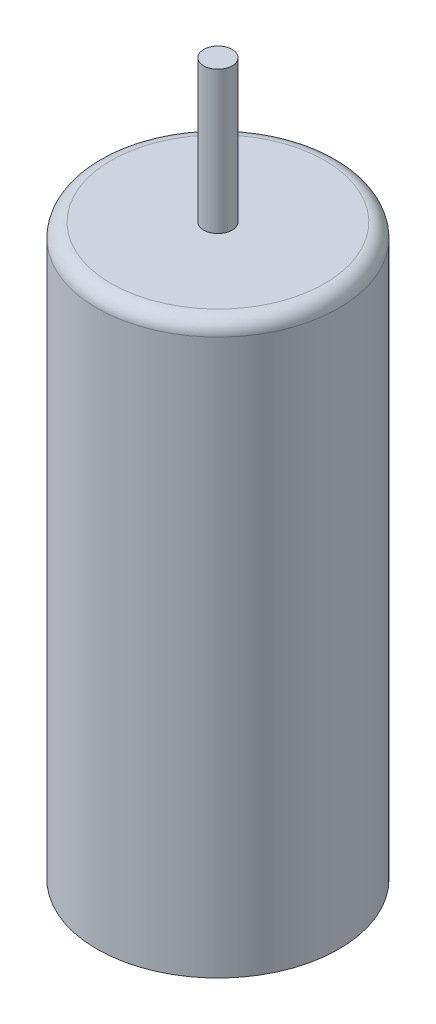
SolidWorks part; units mm, degrees
ref_plane "Front Plane" through (0, 0, 0) normal (0, 0, 1) x (1, 0, 0)
ref_plane "Top Plane" through (0, 0, 0) normal (0, 1, 0) x (1, 0, 0)
ref_plane "Right Plane" through (0, 0, 0) normal (1, 0, 0) x (0, 0, -1)
sketch "Croquis1" plane through (0, 0, 0) normal (0, 1, 0) x (1, 0, 0)
  circle A0 centre (0, 0) radius 4.25
  dimension "D1" = 8.5
extrude "Saliente-Extruir1" add sketch "Croquis1" along normal blind 20
fillet "Redondeo1" radius 0.5 1 edges at (0, 20, 4.25)
sketch "Croquis2" plane through (0, 20, 0) normal (0, 1, 0) x (1, 0, 0)
  circle A0 centre (0, 0) radius 0.5
  dimension "D1" = 1
extrude "Saliente-Extruir2" add sketch "Croquis2" along normal blind 5
